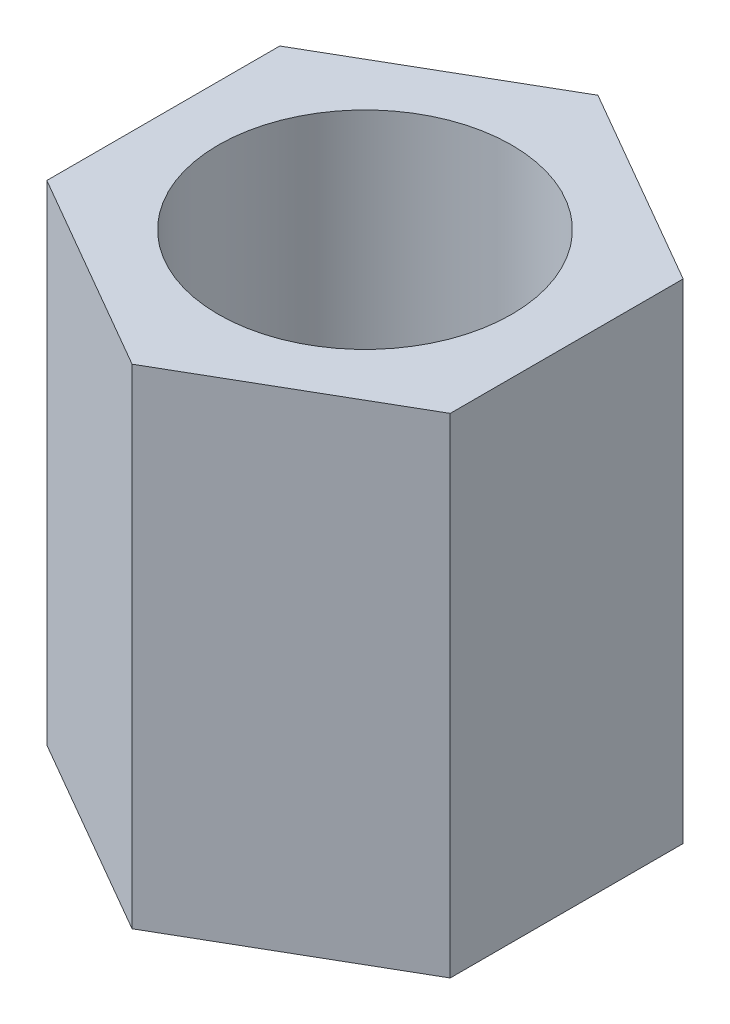
SolidWorks part; units mm, degrees
ref_plane "Front" through (0, 0, 0) normal (0, 0, 1) x (1, 0, 0)
ref_plane "Top" through (0, 0, 0) normal (0, 1, 0) x (1, 0, 0)
ref_plane "Right" through (0, 0, 0) normal (1, 0, 0) x (0, 0, -1)
sketch "草图1" plane through (0, 0, 0) normal (0, 1, 0) x (1, 0, 0)
  line L1 (0, 4.7631) -> (-4.125, 2.3816)
  line L2 (-4.125, 2.3816) -> (-4.125, -2.3816)
  line L3 (-4.125, -2.3816) -> (0, -4.7631)
  line L4 (0, -4.7631) -> (4.125, -2.3816)
  line L5 (4.125, -2.3816) -> (4.125, 2.3816)
  line L6 (4.125, 2.3816) -> (0, 4.7631)
  circle A0 centre (0, 0) radius 3
  circle A1 centre (0, 0) radius 4.125 construction
  point P3 (0, 0)
  dimension "D1" = 6
  dimension "D2" = 8.25
extrude "凸台-拉伸1" add sketch "草图1" along normal blind 10
